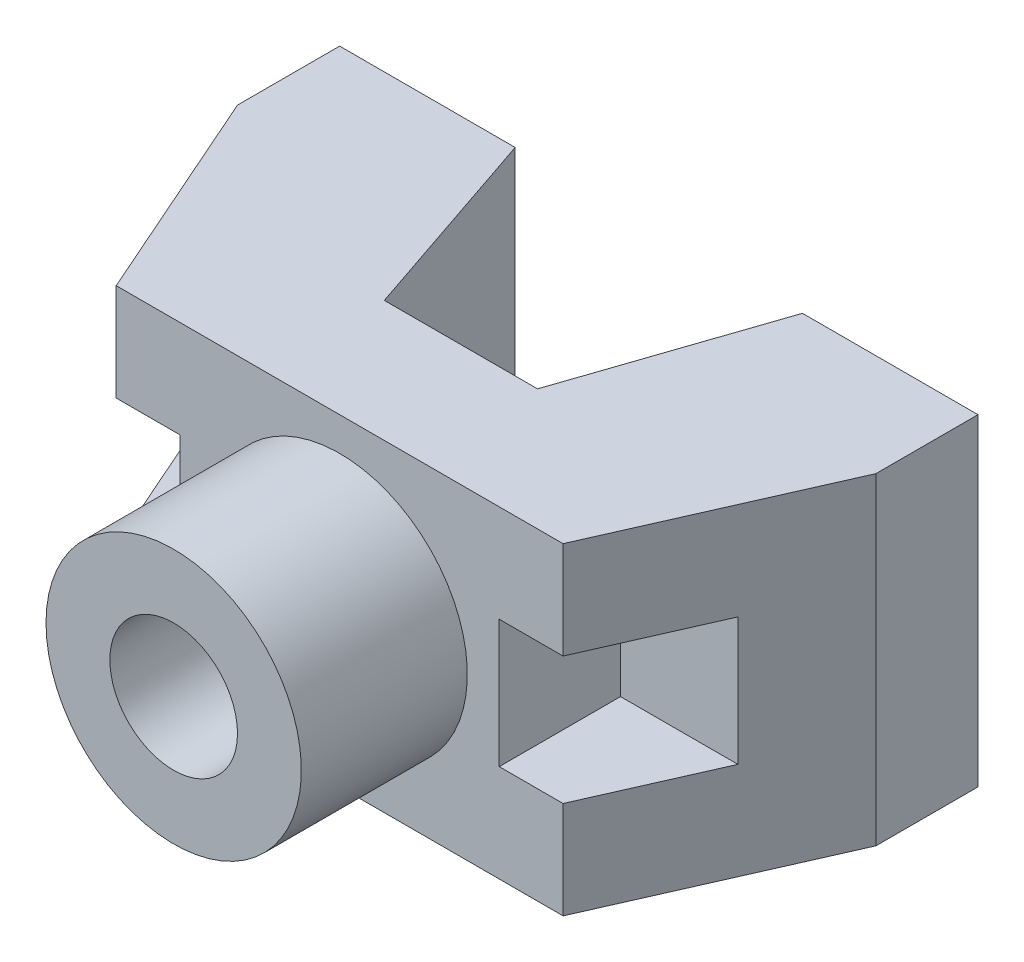
SolidWorks part; units mm, degrees
ref_plane "Front Plane" through (0, 0, 0) normal (0, 0, 1) x (1, 0, 0)
ref_plane "Top Plane" through (0, 0, 0) normal (0, 1, 0) x (1, 0, 0)
ref_plane "Right Plane" through (0, 0, 0) normal (1, 0, 0) x (0, 0, -1)
sketch "Sketch4" plane through (0, 0, 0) normal (0, 1, 0) x (1, 0, 0)
  line L0 (0, 0) -> (70, 0)
  line L12 (0, 0) -> (-15, 34)
  line L14 (-15, 34) -> (-15, 50)
  line L16 (-15, 50) -> (12.5, 50)
  line L21 (12.5, 50) -> (23, 19)
  line L23 (23, 19) -> (47, 19)
  line L25 (70, 0) -> (85, 34)
  line L26 (85, 34) -> (85, 50)
  line L27 (85, 50) -> (57.5, 50)
  line L28 (57.5, 50) -> (47, 19)
  point P5 (35, 19)
  dimension "D2" = 24
  dimension "D3" = 16
  dimension "D4" = 27.5
  dimension "D5" = 70
  dimension "D6" = 100
  dimension "D7" = 50
  dimension "D8" = 45
  dimension "D9" = 15
  dimension "D10" = 19
  dimension "D11" = 23
extrude "Boss-Extrude3" add sketch "Sketch4" along normal blind 50.5 contours L16 L21 L23 L28 L27 L26 L25 L0 L12 L14
sketch "Sketch6" plane through (0, 0, 0) normal (0, 0, 1) x (1, 0, 0)
  line L0 (35, 0) -> (35, 25.25) construction
  line L1 (0, 0) -> (70, 0) construction
  circle A1 centre (35, 25.25) radius 20
  dimension "D3" = 40
  dimension "D1" = 25.25
extrude "Boss-Extrude4" add sketch "Sketch6" along normal blind 26 contours A1
sketch "Sketch7" plane through (0, 0, 26) normal (0, 0, 1) x (1, 0, 0)
  circle A0 centre (35, 25.25) radius 10
  dimension "D1" = 20
extrude "Cut-Extrude1" cut sketch "Sketch7" against normal blind 26
sketch "Sketch8" plane through (0, 0, 0) normal (0, 0, 1) x (1, 0, 0)
  line L0 (70, 50.5) -> (70, 0) construction
  line L2 (80, 25.8555) -> (80, 35.25)
  line L3 (80, 35.25) -> (60, 35.25)
  line L4 (60, 35.25) -> (60, 15.25)
  line L5 (60, 15.25) -> (80, 15.25)
  line L6 (80, 15.25) -> (80, 25.8555)
  line L7 (35, 0) -> (35, 50.5) construction
  line L8 (0, 0) -> (70, 0) construction
  line L9 (0, 50.5) -> (70, 50.5) construction
  line L10 (-10, 25.8555) -> (-10, 35.25)
  line L11 (-10, 15.25) -> (-10, 25.8555)
  line L12 (10, 15.25) -> (-10, 15.25)
  line L13 (10, 35.25) -> (10, 15.25)
  line L14 (-10, 35.25) -> (10, 35.25)
  dimension "D1" = 10
  dimension "D2" = 10
  dimension "D3" = 15.25
  dimension "D4" = 20
extrude "Cut-Extrude2" cut sketch "Sketch8" against normal blind 19
